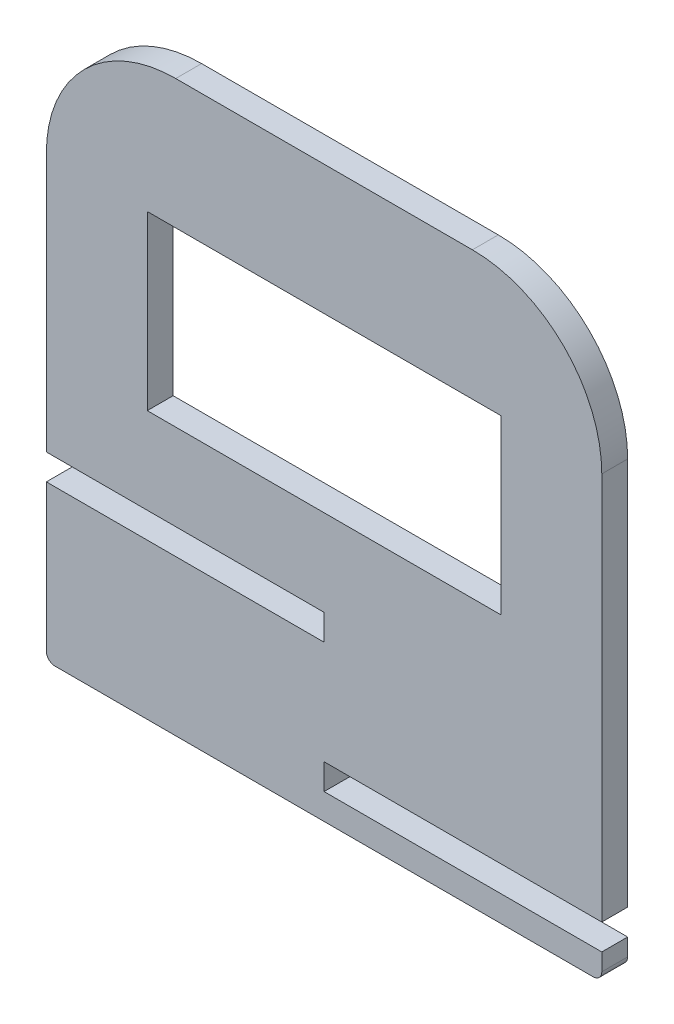
SolidWorks part; units mm, degrees
ref_plane "Front Plane" through (0, 0, 0) normal (0, 0, 1) x (1, 0, 0)
ref_plane "Top Plane" through (0, 0, 0) normal (0, 1, 0) x (1, 0, 0)
ref_plane "Right Plane" through (0, 0, 0) normal (1, 0, 0) x (0, 0, -1)
sketch "Sketch1" plane through (0, 0, 0) normal (0, 0, 1) x (1, 0, 0)
  line L0 (-49.6615, -6.4209) -> (-15.2615, -6.4209)
  line L8 (-52.9615, -21.4209) -> (-11.9615, -21.4209)
  line L9 (-52.9615, -21.4209) -> (-52.9615, -41.4209)
  line L10 (-52.9615, -41.4209) -> (-11.9615, -41.4209)
  line L11 (-11.9615, -21.4209) -> (-11.9615, -41.4209)
  line L12 (-64.6615, -21.4209) -> (-64.6615, -51.4209)
  line L13 (-64.6615, -51.4209) -> (-32.4615, -51.4209)
  line L15 (-64.6615, -54.4209) -> (-32.4615, -54.4209)
  line L16 (-32.4615, -51.4209) -> (-32.4615, -54.4209)
  line L17 (-0.2615, -66.4209) -> (-32.4615, -66.4209)
  line L19 (-0.2615, -69.4209) -> (-32.4615, -69.4209)
  line L20 (-32.4615, -66.4209) -> (-32.4615, -69.4209)
  line L21 (-64.6615, -54.4209) -> (-64.6615, -71.4209)
  line L22 (-0.2615, -21.4209) -> (-0.2615, -66.4209)
  line L23 (-0.2615, -69.4209) -> (-0.2615, -71.4209)
  line L24 (-63.6615, -72.4209) -> (-1.2615, -72.4209)
  arc A0 (-15.2615, -6.4209) -> (-0.2615, -21.4209) centre (-15.2615, -21.4209) cw
  arc A2 (-49.6615, -6.4209) -> (-64.6615, -21.4209) centre (-49.6615, -21.4209) ccw
  arc A3 (-64.6615, -71.4209) -> (-63.6615, -72.4209) centre (-63.6615, -71.4209) ccw
  arc A4 (-1.2615, -72.4209) -> (-0.2615, -71.4209) centre (-1.2615, -71.4209) ccw
  point P24 (0, 0)
  point P28 (-32.4615, -6.4209)
  point P29 (-32.4615, -21.4209)
  dimension "D1" = 41
  dimension "D9" = 64.4
  dimension "D2" = 20
  dimension "D3" = 15
  dimension "D4" = 30
  dimension "D5" = 15
  dimension "D6" = 2
  dimension "D7" = 32.2
  dimension "D8" = 3
  dimension "D10" = 32.2
  dimension "D11" = 3
extrude "Boss-Extrude7" add sketch "Sketch1" along normal blind 3 contours L11 L8 L9 L10 | L23 A4 L24 A3 L21 L15 L16 L13 L12 A2 L0 A0 L22 L17 L20 L19
